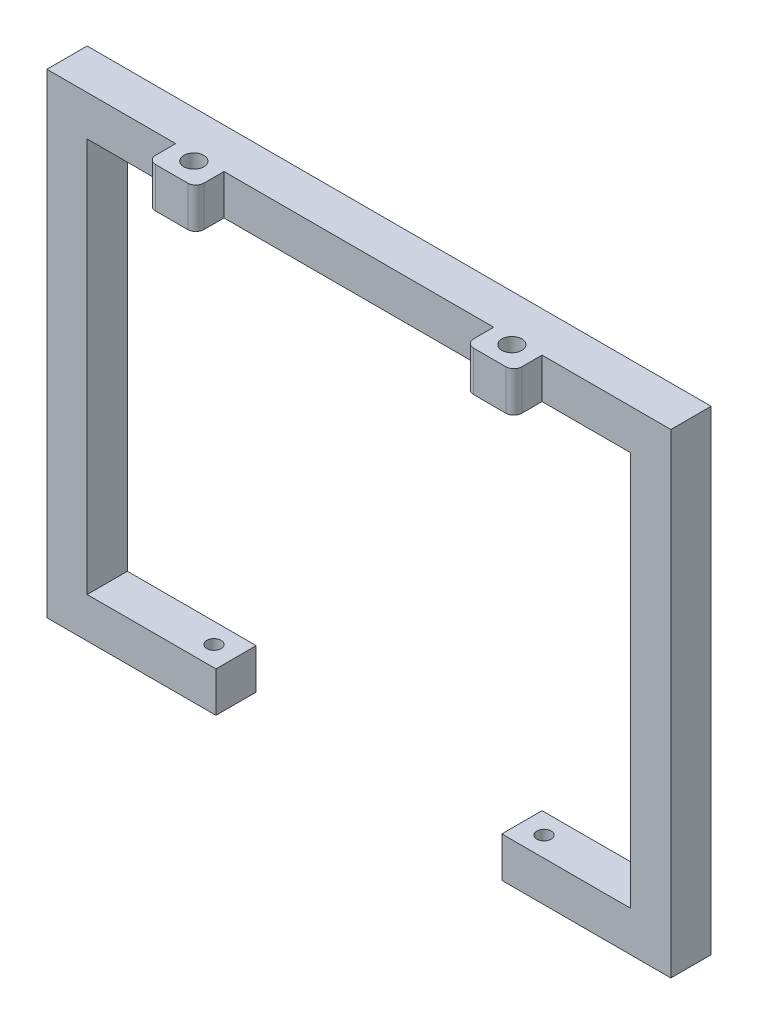
SolidWorks part; units mm, degrees
ref_plane "Front Plane" through (0, 0, 0) normal (0, 0, 1) x (1, 0, 0)
ref_plane "Top Plane" through (0, 0, 0) normal (0, 1, 0) x (1, 0, 0)
ref_plane "Right Plane" through (0, 0, 0) normal (1, 0, 0) x (0, 0, -1)
sketch "Sketch1" plane through (0, 0, 0) normal (0, 0, 1) x (1, 0, 0)
  line L0 (-79.3416, -34.3728) -> (-79.3416, -44.3728)
  line L1 (-79.3416, -44.3728) -> (-121.3416, -44.3728)
  line L2 (-121.3416, -44.3728) -> (-121.3416, 73.6272)
  line L3 (-121.3416, 73.6272) -> (33.6584, 73.6272)
  line L4 (33.6584, 73.6272) -> (33.6584, -44.3728)
  line L5 (33.6584, -44.3728) -> (-8.3416, -44.3728)
  line L6 (-8.3416, -44.3728) -> (-8.3416, -34.3728)
  line L7 (-8.3416, -34.3728) -> (23.6584, -34.3728)
  line L8 (23.6584, -34.3728) -> (23.6584, 63.6272)
  line L9 (23.6584, 63.6272) -> (-111.3416, 63.6272)
  line L10 (-111.3416, 63.6272) -> (-111.3416, -34.3728)
  line L11 (-111.3416, -34.3728) -> (-79.3416, -34.3728)
  line L12 (-111.3416, -34.3728) -> (-121.3416, -34.3728) construction
  line L13 (-111.3416, 63.6272) -> (-111.3416, 73.6272) construction
  line L14 (23.6584, 63.6272) -> (33.6584, 63.6272) construction
  dimension "D1" = 135
  dimension "D2" = 108
  dimension "D3" = 71
  dimension "D4" = 10
extrude "Boss-Extrude1" add sketch "Sketch1" along normal blind 10
sketch "Sketch3" plane through (0, -34.3728, 0) normal (0, 1, 0) x (1, 0, 0)
  line L0 (-84.8416, -5) -> (-79.3416, -5) construction
  line L1 (-79.3416, -10) -> (-79.3416, 0) construction
  line L2 (-8.3416, -5) -> (-2.8416, -5) construction
  line L3 (-8.3416, -10) -> (-8.3416, 0) construction
  circle A0 centre (-84.8416, -5) radius 1.775
  circle A1 centre (-2.8416, -5) radius 1.775
  dimension "D1" = 3.55
  dimension "D2" = 82
extrude "Cut-Extrude2" cut sketch "Sketch3" against normal through all
sketch "Sketch4" plane through (0, 0, 10) normal (0, 0, 1) x (1, 0, 0)
  line L0 (33.6584, 73.6272) -> (-121.3416, 73.6272) construction
  line L1 (-89.3416, 73.6272) -> (-77.3416, 73.6272)
  line L2 (-89.3416, 73.6272) -> (-89.3416, 63.6272)
  line L3 (-89.3416, 63.6272) -> (-77.3416, 63.6272)
  line L4 (-77.3416, 73.6272) -> (-77.3416, 63.6272)
  line L5 (-111.3416, 63.6272) -> (23.6584, 63.6272) construction
  line L6 (-121.3416, 73.6272) -> (-89.3416, 73.6272) construction
  line L7 (-10.3416, 73.6272) -> (1.6584, 73.6272)
  line L8 (-10.3416, 73.6272) -> (-10.3416, 63.6272)
  line L9 (-10.3416, 63.6272) -> (1.6584, 63.6272)
  line L10 (1.6584, 73.6272) -> (1.6584, 63.6272)
  line L11 (1.6584, 73.6272) -> (33.6584, 73.6272) construction
  line L12 (-83.3416, 73.6272) -> (-83.3416, 63.6272) construction
  line L13 (-4.3416, 73.6272) -> (-4.3416, 63.6272) construction
  dimension "D1" = 12
  dimension "D2" = 79
extrude "Boss-Extrude2" add sketch "Sketch4" along normal blind 7
sketch "Sketch5" plane through (0, 73.6272, 0) normal (0, 1, 0) x (1, 0, 0)
  line L0 (-83.3416, -11.5) -> (-4.3416, -11.5) construction
  line L1 (-83.3416, -17) -> (-83.3416, -11.5) construction
  line L2 (-77.3416, -17) -> (-89.3416, -17) construction
  line L3 (-4.3416, -17) -> (-4.3416, -11.5) construction
  line L4 (1.6584, -17) -> (-10.3416, -17) construction
  line L5 (-121.3416, -5) -> (33.6584, -5) construction
  line L6 (-121.3416, -10) -> (-121.3416, 0) construction
  line L7 (33.6584, -10) -> (33.6584, 0) construction
  circle A0 centre (-83.3416, -11.5) radius 2.4798
  circle A1 centre (-4.3416, -11.5) radius 2.4798
  dimension "D1" = 6.5
extrude "Cut-Extrude3" cut sketch "Sketch5" against normal up to surface (10 mm away) up to face at (-48.4666, 63.6272, 11.25)
fillet "Fillet1" radius 2 2 edges at (-77.3416, 68.6272, 17) (-89.3416, 68.6272, 17)
fillet "Fillet2" radius 2 2 edges at (1.6584, 68.6272, 17) (-10.3416, 68.6272, 17)
